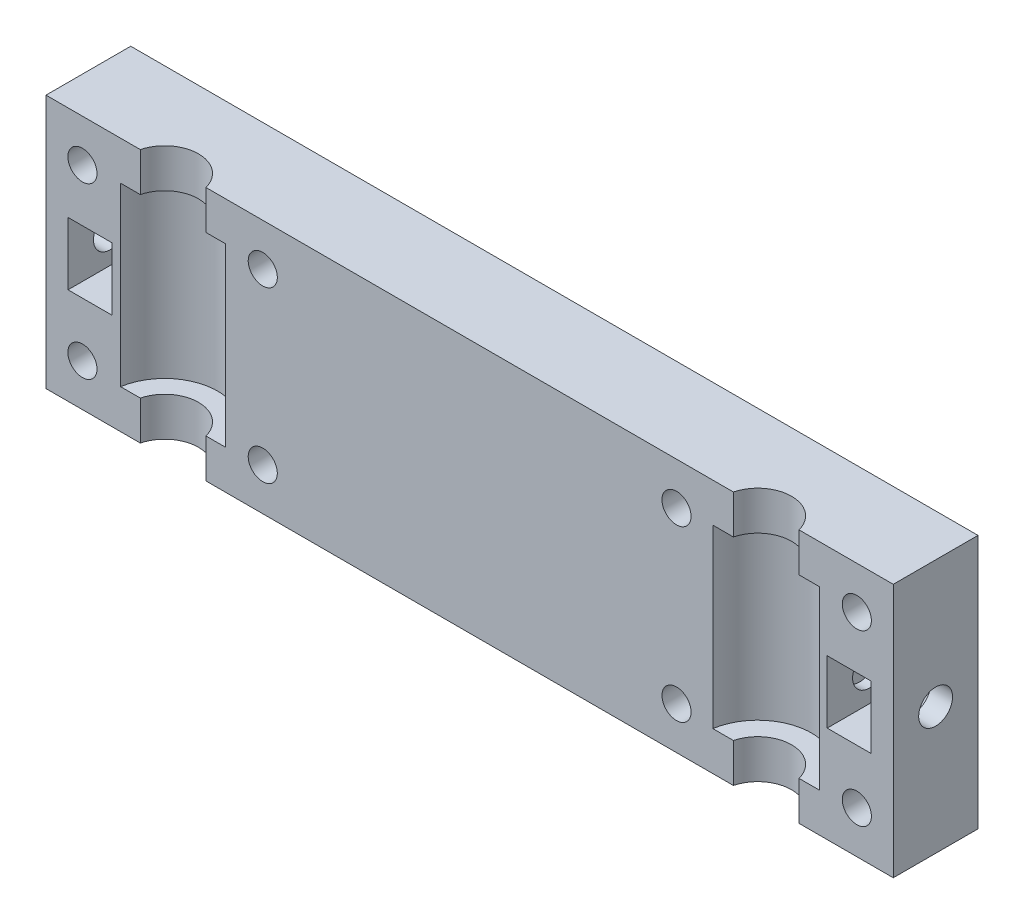
SolidWorks part; units mm, degrees
ref_plane "Front Plane" through (0, 0, 0) normal (0, 0, 1) x (1, 0, 0)
ref_plane "Top Plane" through (0, 0, 0) normal (0, 1, 0) x (1, 0, 0)
ref_plane "Right Plane" through (0, 0, 0) normal (1, 0, 0) x (0, 0, -1)
sketch "Sketch1" plane through (0, 0, 0) normal (0, 1, 0) x (1, 0, 0)
  line L1 (-63.5, 0) -> (63.5, 0)
  line L2 (-63.5, 0) -> (-63.5, -12.7)
  line L3 (-63.5, -12.7) -> (63.5, -12.7)
  line L4 (63.5, 0) -> (63.5, -12.7)
  dimension "D1" = 12.7
  dimension "D2" = 127
  dimension "D3" = 12.7
  dimension "D4" = 63.5
extrude "Boss-Extrude1" add sketch "Sketch1" along normal blind 38.1
sketch "Sketch3" plane through (0, 0, 0) normal (0, 0, -1) x (-1, 0, 0)
  line L0 (-58.039, 38.1) -> (-58.039, 0)
  line L1 (-63.5, 38.1) -> (63.5, 38.1) construction
  line L2 (-63.5, 0) -> (63.5, 0) construction
  line L3 (-63.5, 38.1) -> (-63.5, 0) construction
  line L8 (-44.5241, 38.1) -> (-44.5241, 0)
  line L9 (-31.0092, 38.1) -> (-31.0092, 0)
  line L10 (0, 0) -> (0, 38.1)
  line L11 (31.0092, 38.1) -> (31.0092, 0)
  line L12 (58.039, 38.1) -> (58.039, 0)
  circle A0 centre (-58.039, 31.75) radius 4.445
  circle A1 centre (-58.039, 6.35) radius 4.445
  circle A2 centre (-31.0092, 31.75) radius 4.445
  circle A3 centre (-31.0092, 6.35) radius 4.445
  circle A4 centre (31.0092, 31.75) radius 4.445
  circle A5 centre (31.0092, 6.35) radius 4.445
  circle A6 centre (58.039, 31.75) radius 4.445
  circle A7 centre (58.039, 6.35) radius 4.445
  point P8 (-58.039, 31.75)
  point P9 (-58.039, 6.35)
  point P14 (-31.0092, 6.35)
  point P15 (-31.0092, 31.75)
  point P22 (31.0092, 31.75)
  point P23 (31.0092, 6.35)
  point P24 (58.039, 6.35)
  point P25 (58.039, 31.75)
  dimension "D5" = 8.89
  dimension "D6" = 8.89
  dimension "D7" = 8.89
  dimension "D8" = 8.89
  dimension "D9" = 8.89
  dimension "D10" = 8.89
  dimension "D11" = 8.89
  dimension "D12" = 8.89
  dimension "D1" = 5.461
  dimension "D2" = 6.35
  dimension "D3" = 6.35
  dimension "D4" = 18.9759
extrude "Cut-Extrude3" cut sketch "Sketch3" against normal blind 2.54 contours A2 | A1 | A0 | A6 | A7 | A5 | A4 | A3
ref_plane "Plane2" through (0, 19.05, 0) normal (0, 1, 0) x (1, 0, 0)
sketch "Sketch2" plane through (0, 19.05, 0) normal (0, 1, 0) x (1, 0, 0)
  line L2 (-63.5, 0) -> (-63.5, -12.7) construction
  line L6 (63.5, 0) -> (-63.5, 0) construction
  circle A0 centre (-44.45, -13.97) radius 7.9756
  circle A1 centre (44.45, -13.97) radius 8.1026
  dimension "D1" = 15.9512
  dimension "D4" = 16.2052
  dimension "D2" = 88.9
  dimension "D3" = 19.05
  dimension "D5" = 13.97
  dimension "D6" = 13.97
extrude "Cut-Extrude4" cut sketch "Sketch2" against normal blind 13.208 and the other way blind 13.208
sketch "Sketch6" plane through (0, 38.1, 0) normal (0, 1, 0) x (1, 0, 0)
  circle A0 centre (-44.45, -13.97) radius 5.08
  circle A1 centre (44.45, -13.97) radius 5.08
  dimension "D1" = 10.16
  dimension "D2" = 10.16
extrude "Cut-Extrude5" cut sketch "Sketch6" against normal blind 38.1
hole_wizard "11/64 (0.17188) Diameter Hole1" positions "3DSketch1" profile "Sketch7" hole size "11/64" standard "ANSI Inch"
sketch3d "3DSketch1"
  line L0 (58.039, 31.75, 2.54) -> (58.039, 31.75, 0) construction
  line L1 (58.039, 6.35, 2.54) -> (58.039, 6.35, 0) construction
  line L2 (31.0092, 31.75, 2.54) -> (31.0092, 31.75, 0) construction
  line L3 (31.0092, 6.35, 2.54) -> (31.0092, 6.35, 0) construction
  line L4 (-31.0092, 31.75, 2.54) -> (-31.0092, 31.75, 0) construction
  line L5 (-31.0092, 6.35, 2.54) -> (-31.0092, 6.35, 0) construction
  line L6 (-58.039, 6.35, 2.54) -> (-58.039, 6.35, 0) construction
  line L7 (-58.039, 31.75, 2.54) -> (-58.039, 31.75, 0) construction
  point P0 (58.039, 31.75, 0)
  point P4 (58.039, 6.35, 2.54)
  point P8 (31.0092, 31.75, 0)
  point P12 (31.0092, 6.35, 0)
  point P16 (-31.0092, 31.75, 2.54)
  point P20 (-31.0092, 6.35, 0)
  point P24 (-58.039, 6.35, 2.54)
  point P28 (-58.039, 31.75, 0)
sketch "Sketch7" plane through (58.039, 31.75, 0) normal (1, 0, 0) x (0, 1, 0)
  line L0 (0, 0) -> (0, 26.7116)
  line L1 (0, 26.7116) -> (2.1829, 25.4)
  line L2 (2.1829, 25.4) -> (2.1829, 0)
  line L5 (2.1829, 0) -> (0, 0)
  line L10 (0, 26.7116) -> (-2.1829, 25.4) construction
  line L11 (0, -6.35) -> (0, 107.95) construction
  dimension "Hole Dia." = 4.3658
  dimension "Hole Depth" = 25.4
  dimension "Drill Angle" = 118
sketch "Sketch9" plane through (-63.5, 0, 0) normal (-1, 0, 0) x (0, 0, 1)
  line L0 (12.7, 38.1) -> (12.7, 0) construction
  circle A0 centre (6.35, 19.05) radius 2.54
  dimension "D2" = 5.08
  dimension "D1" = 19.05
  dimension "D3" = 6.35
extrude "Cut-Extrude7" cut sketch "Sketch9" against normal blind 11.43 contours A0
sketch "Sketch10" plane through (0, 0, 12.7) normal (0, 0, 1) x (1, 0, 0)
  line L0 (-63.5, 0) -> (-49.3687, 0) construction
  line L1 (-60.1978, 23.876) -> (-53.5938, 23.876)
  line L2 (-60.1978, 23.876) -> (-60.1978, 14.478)
  line L3 (-60.1978, 14.478) -> (-53.5938, 14.478)
  line L4 (-53.5938, 23.876) -> (-53.5938, 14.478)
  line L7 (-52.3238, 32.258) -> (-52.3238, 5.842) construction
  line L8 (0, 0) -> (0, 38.1)
  line L9 (-39.5313, 38.1) -> (39.5313, 38.1) construction
  line L10 (53.5938, 23.876) -> (53.5938, 14.478)
  line L11 (60.1978, 14.478) -> (53.5938, 14.478)
  line L12 (60.1978, 23.876) -> (60.1978, 14.478)
  line L13 (60.1978, 23.876) -> (53.5938, 23.876)
  dimension "D1" = 14.478
  dimension "D2" = 6.604
  dimension "D3" = 9.398
  dimension "D4" = 1.27
extrude "Cut-Extrude10" cut sketch "Sketch10" against normal through all contours L4 L1 L2 L3 | L12 L13 L10 L11 | L8
sketch "Sketch11" plane through (63.5, 0, 0) normal (1, 0, 0) x (0, 0, -1)
  line L0 (-12.7, 0) -> (0, 0) construction
  line L1 (0, 38.1) -> (0, 0) construction
  circle A0 centre (-6.35, 19.05) radius 2.54
  dimension "D2" = 5.08
  dimension "D1" = 19.05
  dimension "D3" = 6.35
extrude "Cut-Extrude11" cut sketch "Sketch11" against normal blind 11.43
